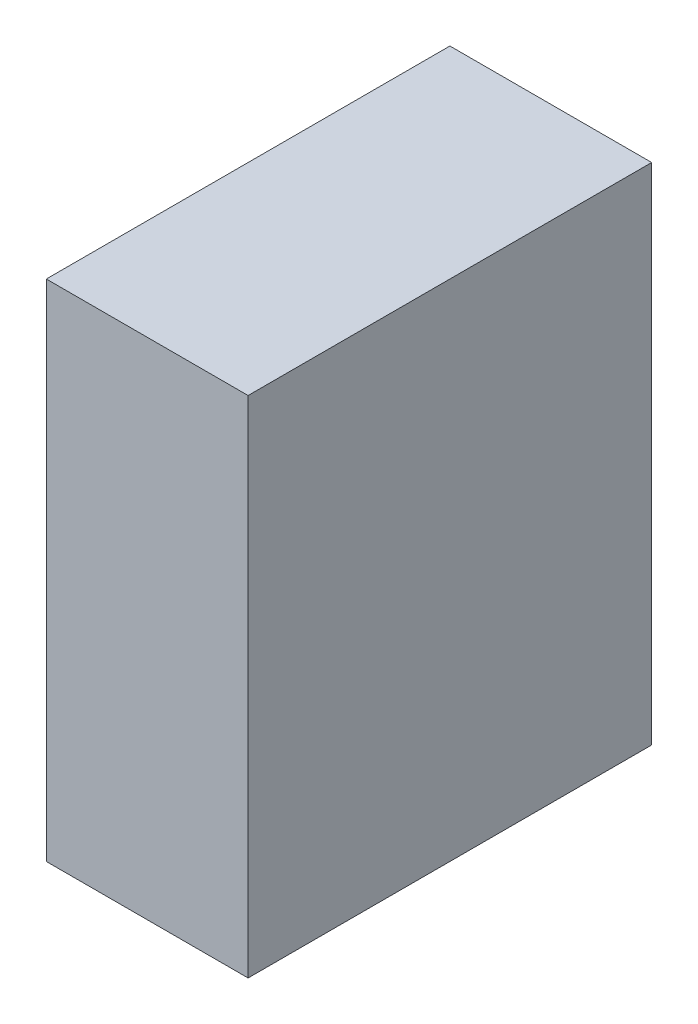
SolidWorks part; units mm, degrees
ref_plane "Front Plane" through (0, 0, 0) normal (0, 0, 1) x (1, 0, 0)
ref_plane "Top Plane" through (0, 0, 0) normal (0, 1, 0) x (1, 0, 0)
ref_plane "Right Plane" through (0, 0, 0) normal (1, 0, 0) x (0, 0, -1)
sketch "Sketch1" plane through (0, 0, 0) normal (0, 1, 0) x (1, 0, 0)
  line L1 (-20, 40) -> (20, 40)
  line L2 (-20, 40) -> (-20, -40)
  line L3 (-20, -40) -> (20, -40)
  line L4 (20, 40) -> (20, -40)
  line L5 (-20, 40) -> (20, -40) construction
  line L6 (-20, -40) -> (20, 40) construction
  point P0 (0, 0)
  dimension "D1" = 40
  dimension "D2" = 80
extrude "Boss-Extrude1" add sketch "Sketch1" along normal blind 100
sketch "Sketch3" plane through (0, 0, 0) normal (0, -1, 0) x (1, 0, 0)
  circle A0 centre (0, 0) radius 10
  circle A1 centre (0, 22) radius 5
  circle A2 centre (0, -22) radius 5
  dimension "D1" = 20
  dimension "D2" = 10
  dimension "D3" = 10
  dimension "D4" = 22
  dimension "D5" = 22
extrude "Cut-Extrude2" cut sketch "Sketch3" against normal blind 20
sketch "Sketch6" plane through (0, 100, 0) normal (0, 1, 0) x (1, 0, 0)
  line L0 (-20, -40) -> (20, -40) construction
  line L1 (-20, 40) -> (20, 40)
  line L2 (-20, 40) -> (-20, -40)
  line L3 (-20, -40) -> (20, -40)
  line L4 (20, 40) -> (20, -40)
  line L5 (-20, 40) -> (20, -40) construction
  line L6 (-20, -40) -> (20, 40) construction
  line L7 (20, -40) -> (20, 40) construction
  point P0 (0, 0)
